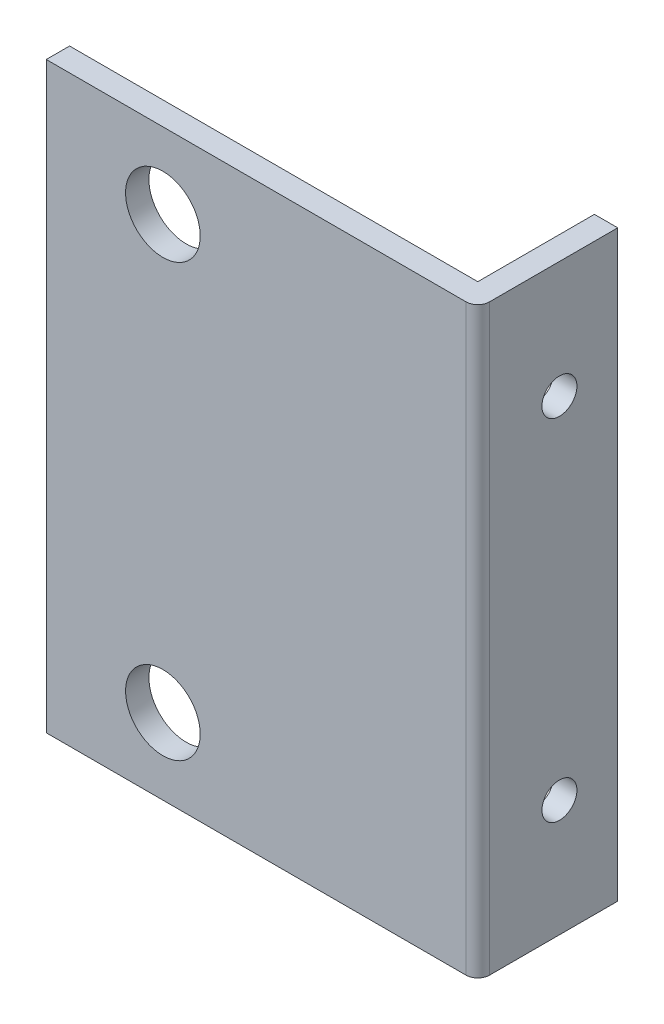
SolidWorks part; units mm, degrees
ref_plane "Front Plane" through (0, 0, 0) normal (0, 0, 1) x (1, 0, 0)
ref_plane "Top Plane" through (0, 0, 0) normal (0, 1, 0) x (1, 0, 0)
ref_plane "Right Plane" through (0, 0, 0) normal (1, 0, 0) x (0, 0, -1)
sketch "Sketch3" plane through (0, 0, 0) normal (0, 1, 0) x (1, 0, 0)
  line L0 (0, 0) -> (37, 0)
  line L1 (37, 0) -> (37, 12)
  line L2 (37, 12) -> (35, 12)
  line L3 (35, 12) -> (35, 2)
  line L4 (35, 2) -> (0, 2)
  line L5 (0, 2) -> (0, 0)
  dimension "D1" = 37
  dimension "D2" = 2
  dimension "D3" = 2
  dimension "D4" = 12
extrude "Boss-Extrude1" add sketch "Sketch3" along normal blind 50
fillet "Fillet2" radius 1 1 edges at (37, 25, 0)
sketch "Sketch4" plane through (37, 0, 0) normal (1, 0, 0) x (0, 0, -1)
  line L0 (12, 25) -> (1.2368, 25) construction
  line L1 (12, 50) -> (12, 0) construction
  circle A0 centre (7, 40) radius 1.5
  circle A1 centre (7, 10) radius 1.5
  dimension "D1" = 3
  dimension "D2" = 30
  dimension "D3" = 5
extrude "Cut-Extrude1" cut sketch "Sketch4" against normal through all
sketch "Sketch5" plane through (0, 0, 0) normal (0, 0, 1) x (1, 0, 0)
  line L0 (0, 25) -> (36, 25) construction
  line L1 (0, 50) -> (0, 0) construction
  line L2 (36, 0) -> (36, 50) construction
  circle A0 centre (10, 43.5) radius 3.2
  circle A1 centre (10, 6.5) radius 3.2
  dimension "D1" = 6.4
  dimension "D3" = 10
  dimension "D2" = 18.5
extrude "Cut-Extrude2" cut sketch "Sketch5" against normal through all
